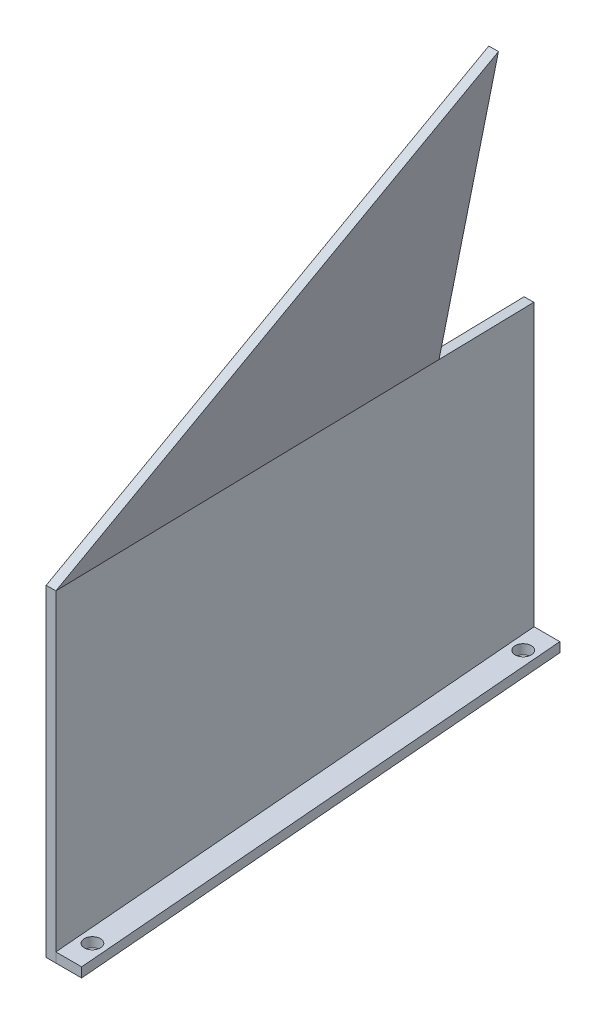
SolidWorks part; units mm, degrees
ref_plane "Front Plane" through (0, 0, 0) normal (0, 0, 1) x (1, 0, 0)
ref_plane "Top Plane" through (0, 0, 0) normal (0, 1, 0) x (1, 0, 0)
ref_plane "Right Plane" through (0, 0, 0) normal (1, 0, 0) x (0, 0, -1)
sketch3d "3DSketch1"
  line L0 (-191.8531, 23, 196.3861) -> (-178.7731, 22.8797, 357.7307)
  line L1 (-178.7731, 22.8797, 357.7307) -> (-178.7731, 122.8797, 357.7307)
  line L2 (-178.7731, 122.8797, 357.7307) -> (-191.8531, 113.1924, 196.3861)
  line L3 (-191.8531, 113.1924, 196.3861) -> (-191.8531, 23, 196.3861)
extrude "Boss-Extrude1" add sketch "3DSketch1" along direction (1, 0, 0) on the side of the normal blind 3
sketch "Sketch1" plane through (0, 23.1464, 0.0173) normal (0, -1, -0.0007) x (1, 0, 0)
  line L0 (-175.7731, 357.7136) -> (-167.7731, 357.7136)
  line L1 (-188.8531, 196.3017) -> (-180.8531, 196.3017)
  line L2 (-180.8531, 196.3017) -> (-167.7731, 357.7136)
  line L3 (-175.7731, 357.7136) -> (-188.8531, 196.3017)
  circle A0 centre (-172.4345, 349.7136) radius 2.5
  circle A1 centre (-184.2179, 204.3017) radius 2.5
  dimension "D1" = 5
  dimension "D2" = 8
  dimension "D3" = 4
  dimension "D4" = 8
  dimension "D5" = 4
  dimension "D6" = 8
extrude "Boss-Extrude2" add sketch "Sketch1" against normal blind 3
sketch3d "3DSketch2"
  line L0 (-189.2588, 24.9214, 228.3872) -> (-178.7731, 22.8797, 357.7307)
  line L1 (-178.7731, 22.8797, 357.7307) -> (-178.7731, 122.8797, 357.7307)
  line L3 (-189.2588, 115.1138, 228.3872) -> (-189.2588, 24.9214, 228.3872)
  line L4 (-189.2588, 115.1138, 228.3872) -> (-158.1318, 219.7436, 241.076)
  line L5 (-158.1318, 219.7436, 241.076) -> (-178.7731, 122.8797, 357.7307)
  line L6 (-189.2588, 115.1138, 228.3872) -> (-178.7731, 122.8797, 357.7307)
  point P2 (0, 0, 0)
  point P3 (0, 0, 0)
  point P5 (-158.1318, 219.7436, 241.076)
  point P10 (0, 0, 0)
  dimension "D1" = 130
extrude "Boss-Extrude5" add sketch "3DSketch2" along direction (1, 0, 0) on the side against the normal blind 3 contours L5 L6 L4
